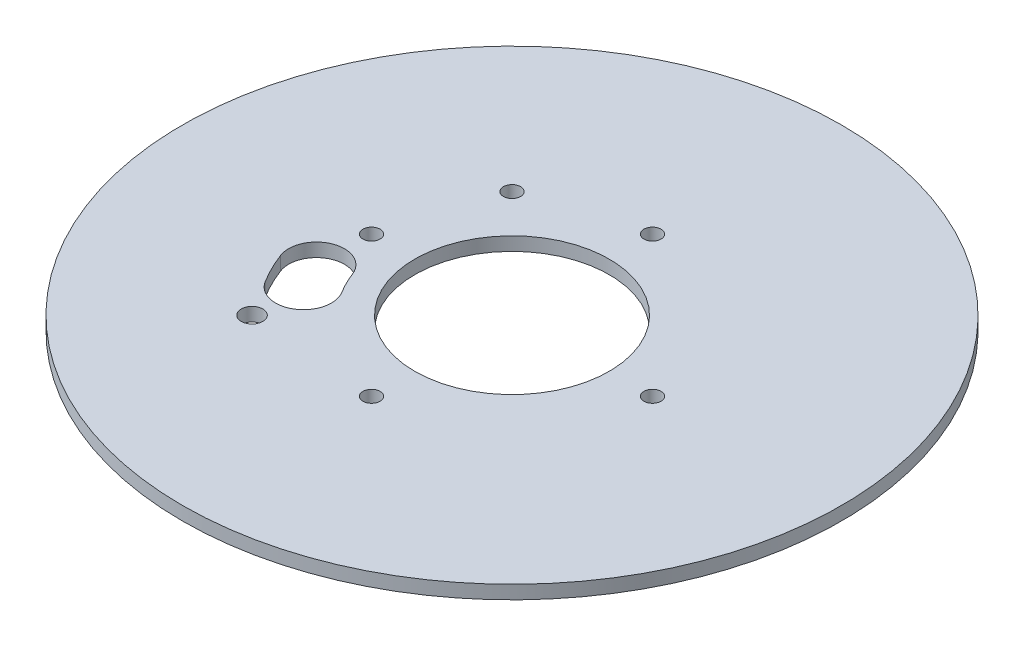
SolidWorks part; units mm, degrees
ref_plane "Front" through (0, 0, 0) normal (0, 0, 1) x (1, 0, 0)
ref_plane "Top" through (0, 0, 0) normal (0, 1, 0) x (1, 0, 0)
ref_plane "Right" through (0, 0, 0) normal (1, 0, 0) x (0, 0, -1)
sketch "Sketch1" plane through (0, 0, 0) normal (0, 1, 0) x (1, 0, 0)
  circle A0 centre (0, 0) radius 77.46
  dimension "D1" = 154.92
extrude "Boss-Extrude1" add sketch "Sketch1" along normal blind 3.175
sketch "Sketch2" plane through (0, 3.175, 0) normal (0, 1, 0) x (1, 0, 0)
  circle A0 centre (0, 0) radius 22.86
  dimension "D1" = 45.72
extrude "Cut-Extrude1" [suppressed] cut sketch "Sketch2" against normal through all
hole_wizard "M3 Clearance Hole1" [suppressed] positions "Sketch4" profile "Sketch3" hole size "M3" standard "ANSI Metric"
sketch "Sketch4" plane through (0, 3.175, 0) normal (0, 1, 0) x (1, 0, 0)
  circle A0 centre (0, 0) radius 27 construction
  point P0 (-27, 0)
  point P2 (0, 27)
  point P4 (27, 0)
  point P6 (0, -27)
  dimension "D1" = 54
sketch "Sketch3" plane through (-27, 3.175, 0) normal (1, 0, 0) x (0, 0, 1)
  line L0 (0, 0) -> (0, 3.175)
  line L1 (0, 3.175) -> (1.7, 3.175)
  line L2 (1.7, 3.175) -> (1.7, 0)
  line L5 (1.7, 0) -> (0, 0)
  line L11 (0, -6.35) -> (0, 107.95) construction
  dimension "Thru Hole Dia." = 3.4
  dimension "Thru Hole Depth" = 3.175
sketch "Sketch5" plane through (0, 0, 0) normal (0, -1, 0) x (-1, 0, 0)
  line L0 (0, 0) -> (116.3694, 0) construction
  line L1 (76.4147, 28.5) -> (66.4147, 28.5)
  line L2 (76.4147, 28.5) -> (76.4147, 31.5)
  line L3 (76.4147, 31.5) -> (66.4147, 31.5)
  line L4 (66.4147, 28.5) -> (66.4147, 31.5)
  line L5 (76.4147, 28.5) -> (66.4147, 31.5) construction
  line L6 (76.4147, 31.5) -> (66.4147, 28.5) construction
  line L7 (76.4147, -28.5) -> (76.4147, -31.5)
  line L8 (76.4147, -28.5) -> (66.4147, -28.5)
  line L9 (66.4147, -28.5) -> (66.4147, -31.5)
  line L10 (76.4147, -31.5) -> (66.4147, -31.5)
  circle A0 centre (0, 0) radius 77.46 construction
  point P0 (71.4147, 30)
  dimension "D1" = 3
  dimension "D2" = 10
  dimension "D3" = 30
extrude "Cut-Extrude2" [suppressed] cut sketch "Sketch5" against normal through all
hole_wizard "M3 Clearance Slot1" [suppressed] positions "Sketch7" profile "Sketch8" size "M3" standard "ANSI Metric"
sketch "Sketch7" plane through (0, 0, 0) normal (0, -1, 0) x (-1, 0, 0)
  line L0 (0, 0) -> (71.3755, 0) construction
  line L1 (55, -30) -> (25, -30) construction
  point P0 (40, -30)
  dimension "D1" = 40
  dimension "D2" = 30
  dimension "D3" = 30
sketch "Sketch8" plane through (-40, 0, 30) normal (1, 0, 0) x (0, 0, -1)
  line L0 (0, 0) -> (0, 26.4215)
  line L1 (0, 26.4215) -> (1.7, 25.4)
  line L2 (1.7, 25.4) -> (1.7, 0)
  line L5 (1.7, 0) -> (0, 0)
  line L10 (0, 26.4215) -> (-1.7, 25.4) construction
  line L11 (0, -6.35) -> (0, 107.95) construction
  dimension "Hole Dia." = 3.4
  dimension "Hole Depth" = 25.4
  dimension "Drill Angle" = 118
hole_wizard "M3 Clearance Hole2" [suppressed] positions "Sketch11" profile "Sketch12" hole size "M3" standard "ANSI Metric"
sketch "Sketch11" [suppressed] plane through (0, 3.175, 0) normal (0, 1, 0) x (1, 0, 0)
  line L0 (-53.3, -28.3) -> (-53.3, 14.1687) construction
  point P0 (-53.3, 30)
  dimension "D1" = 30
sketch "Sketch12" plane through (-53.3, 3.175, -30) normal (1, 0, 0) x (0, 0, 1)
  line L0 (0, 0) -> (0, 3.175)
  line L1 (0, 3.175) -> (1.7, 3.175)
  line L2 (1.7, 3.175) -> (1.7, 0)
  line L5 (1.7, 0) -> (0, 0)
  line L11 (0, -6.35) -> (0, 107.95) construction
  dimension "Thru Hole Dia." = 3.4
  dimension "Thru Hole Depth" = 3.175
sketch "Sketch13" [suppressed] plane through (0, 3.175, 0) normal (0, 1, 0) x (1, 0, 0)
  line L0 (0, 0) -> (0, 33.02) construction
  circle A0 centre (0, 0) radius 33.02 construction
  circle A1 centre (0, 0) radius 22.86 construction
  circle A2 centre (0, 33.02) radius 2.0193
  circle A3 centre (33.02, 0) radius 2.0193
  circle A4 centre (0, -33.02) radius 2.0193
  circle A5 centre (-33.02, 0) radius 2.0193
  point P16 (0, 0)
  dimension "D1" = 10.16
  dimension "D2" = 4.0386
  dimension "D3" = 4
extrude "Cut-Extrude3" [suppressed] cut sketch "Sketch13" against normal up to next
extrude "Cut-Extrude9" [suppressed] cut sketch "Sketch19" against normal through all
sketch "Sketch19" plane through (-73.7688, 25.4, -121.0804) normal (0, 1, 0) x (1, 0, 0)
  circle A1 centre (48.605, -95.9166) radius 2.0193 construction
  circle A3 centre (73.7688, -121.0804) radius 22.86 construction
  circle A4 centre (73.7688, -121.0804) radius 35.587 construction
  arc A5 (40.7129, -134.2614) -> (42.8303, -138.6656) centre (73.7688, -121.0804) ccw construction
  arc A6 (33.7184, -137.0504) -> (36.2838, -142.3866) centre (73.7688, -121.0804) ccw
  arc A7 (47.7074, -131.4723) -> (49.3768, -134.9446) centre (73.7688, -121.0804) ccw
  arc A8 (47.7074, -131.4723) -> (33.7184, -137.0504) centre (40.7129, -134.2614) ccw
  arc A9 (36.2838, -142.3866) -> (49.3768, -134.9446) centre (42.8303, -138.6656) ccw
  point P9 (41.6959, -136.4999)
extrude "Cut-Extrude10" cut sketch "Sketch20" against normal through all
sketch "Sketch20" plane through (-73.7688, 25.4, -121.0804) normal (0, 1, 0) x (1, 0, 0)
  line L0 (73.7688, -121.0804) -> (73.7688, -88.0604) construction
  circle A1 centre (73.7688, -121.0804) radius 77.46 construction
  circle A2 centre (73.7688, -121.0804) radius 22.86
  circle A3 centre (73.7688, -88.0604) radius 2.0193
  circle A4 centre (106.7888, -121.0804) radius 2.0193
  circle A5 centre (73.7688, -154.1004) radius 2.0193
  circle A6 centre (40.7488, -121.0804) radius 2.0193
  point P4 (73.7688, -98.2204)
  point P16 (73.7688, -121.0804)
extrude "Cut-Extrude11" cut sketch "Sketch21" against normal through all
sketch "Sketch21" plane through (-73.7688, 25.4, -121.0804) normal (0, 1, 0) x (1, 0, 0)
  line L0 (43.2169, -90.5284) -> (48.605, -95.9166) construction
  arc A1 (41.4208, -92.3245) -> (45.0129, -88.7324) centre (43.2169, -90.5284) ccw construction
  circle A2 centre (48.605, -95.9166) radius 2.0193
extrude "Cut-Extrude12" cut sketch "Sketch22" against normal through all
sketch "Sketch22" plane through (-73.7688, 25.4, -121.0804) normal (0, 1, 0) x (1, 0, 0)
  circle A2 centre (73.7688, -121.0804) radius 22.86 construction
  circle A3 centre (48.605, -95.9166) radius 2.0193 construction
  circle A4 centre (73.7688, -121.0804) radius 35.587 construction
  arc A5 (40.5263, -133.7834) -> (43.5223, -139.8309) centre (73.7688, -121.0804) ccw construction
  arc A6 (34.406, -136.1222) -> (37.9536, -143.283) centre (73.7688, -121.0804) ccw
  arc A7 (46.6466, -131.4446) -> (49.091, -136.3787) centre (73.7688, -121.0804) ccw
  arc A8 (46.6466, -131.4446) -> (34.406, -136.1222) centre (40.5263, -133.7834) ccw
  arc A9 (37.9536, -143.283) -> (49.091, -136.3787) centre (43.5223, -139.8309) ccw
  point P9 (41.8806, -136.8783)
extrude "Cut-Extrude13" cut sketch "Sketch23" against normal blind 3.175
sketch "Sketch23" plane through (-73.7688, 0, -121.0804) normal (0, -1, 0) x (1, 0, 0)
  arc A1 (41.4208, 149.8362) -> (45.0129, 153.4284) centre (43.2169, 151.6323) ccw construction
  circle A2 centre (43.2169, 151.6323) radius 2.54
